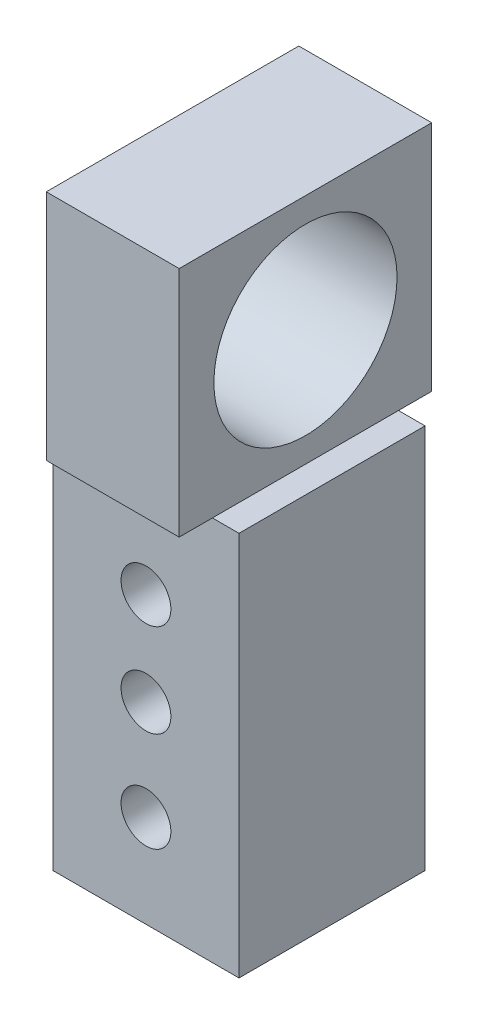
SolidWorks part; units mm, degrees
ref_plane "Front Plane" through (0, 0, 0) normal (0, 0, 1) x (1, 0, 0)
ref_plane "Top Plane" through (0, 0, 0) normal (0, 1, 0) x (1, 0, 0)
ref_plane "Right Plane" through (0, 0, 0) normal (1, 0, 0) x (0, 0, -1)
sketch "Sketch1" plane through (0, 0, 0) normal (0, 1, 0) x (1, 0, 0)
  line L1 (17.78, -17.78) -> (-17.78, -17.78)
  line L2 (17.78, -17.78) -> (17.78, 17.78)
  line L3 (17.78, 17.78) -> (-17.78, 17.78)
  line L4 (-17.78, -17.78) -> (-17.78, 17.78)
  line L5 (17.78, -17.78) -> (-17.78, 17.78) construction
  line L6 (17.78, 17.78) -> (-17.78, -17.78) construction
  point P0 (0, 0)
  dimension "D1" = 35.56
  dimension "D2" = 35.56
extrude "Boss-Extrude1" add sketch "Sketch1" against normal blind 73.5965
sketch "Sketch2" plane through (0, 0, 17.78) normal (0, 0, 1) x (1, 0, 0)
  line L0 (-17.78, 0) -> (17.78, 0) construction
  line L4 (17.78, -73.5965) -> (17.78, 0) construction
  circle A1 centre (0, -19.05) radius 4.7625
  circle A2 centre (0, -36.83) radius 4.7625
  circle A3 centre (0, -55.88) radius 4.7625
  dimension "D4" = 19.05
  dimension "D5" = 9.525
  dimension "D6" = 9.525
  dimension "D7" = 9.525
  dimension "D2" = 17.78
  dimension "D3" = 19.05
  dimension "D8" = 55.88
  dimension "D10" = 17.78
  dimension "D12" = 17.78
extrude "Cut-Extrude1" cut sketch "Sketch2" against normal through all
sketch "Sketch3" plane through (0, 0, 0) normal (0, 1, 0) x (1, 0, 0)
  line L0 (-17.78, -17.78) -> (17.78, -17.78) construction
  line L1 (12.7, 17.78) -> (-12.7, 17.78)
  line L2 (12.7, 17.78) -> (12.7, -17.78)
  line L3 (12.7, -17.78) -> (-12.7, -17.78)
  line L4 (-12.7, 17.78) -> (-12.7, -17.78)
  line L5 (12.7, 17.78) -> (-12.7, -17.78) construction
  line L6 (12.7, -17.78) -> (-12.7, 17.78) construction
  line L7 (-17.78, 17.78) -> (-17.78, -17.78) construction
  line L8 (17.78, -17.78) -> (17.78, 17.78) construction
  point P0 (0, 0)
  dimension "D1" = 30.48
  dimension "D2" = 30.48
  dimension "D3" = 35.56
extrude "Boss-Extrude2" add sketch "Sketch3" along normal blind 44.45
sketch "Sketch5" plane through (0, 0, 17.78) normal (0, 0, 1) x (1, 0, 0)
  line L1 (-12.7, 44.45) -> (12.7, 44.45)
  line L2 (-12.7, 44.45) -> (-12.7, 0)
  line L3 (-12.7, 0) -> (12.7, 0)
  line L4 (12.7, 44.45) -> (12.7, 0)
extrude "Boss-Extrude3" add sketch "Sketch5" along normal blind 6.35
sketch "Sketch6" plane through (0, 0, -17.78) normal (0, 0, -1) x (-1, 0, 0)
  line L1 (-12.7, 44.45) -> (12.7, 44.45)
  line L2 (-12.7, 44.45) -> (-12.7, 0)
  line L3 (-12.7, 0) -> (12.7, 0)
  line L4 (12.7, 44.45) -> (12.7, 0)
extrude "Boss-Extrude4" add sketch "Sketch6" along normal blind 6.35
sketch "Sketch4" plane through (12.7, 0, 0) normal (1, 0, 0) x (0, 0, -1)
  line L0 (-24.13, 44.45) -> (24.13, 44.45) construction
  line L3 (-17.78, 44.45) -> (-17.78, 0) construction
  circle A0 centre (0, 22.225) radius 17.5
  dimension "D1" = 22.225
  dimension "D2" = 35
  dimension "D3" = 17.78
extrude "Cut-Extrude2" cut sketch "Sketch4" against normal through all
